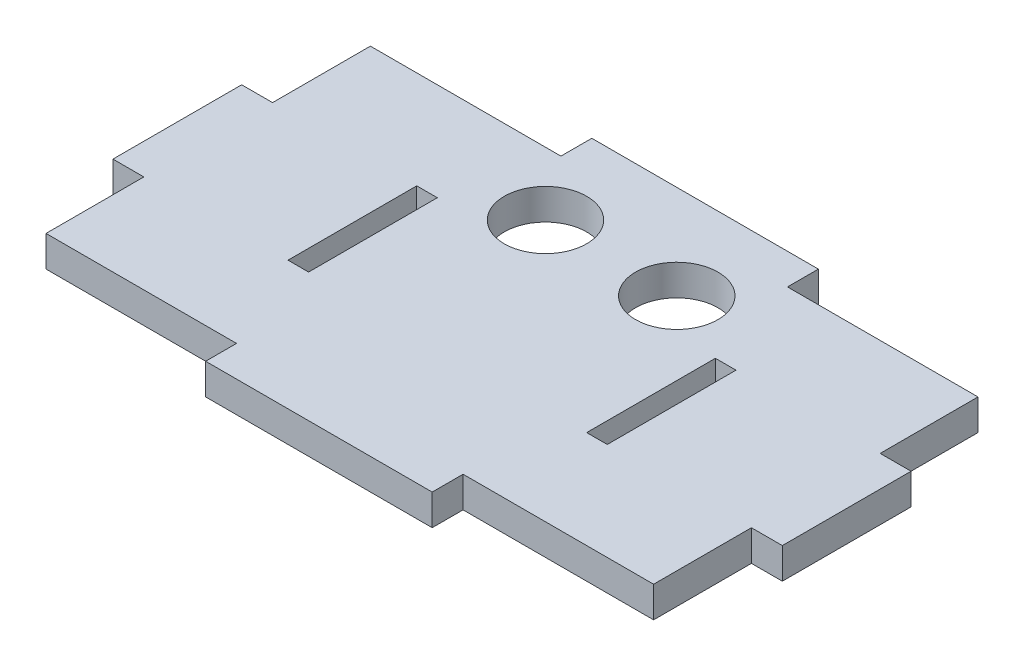
SolidWorks part; units mm, degrees
ref_plane "Front" through (0, 0, 0) normal (0, 0, 1) x (1, 0, 0)
ref_plane "Top" through (0, 0, 0) normal (0, 1, 0) x (1, 0, 0)
ref_plane "Right" through (0, 0, 0) normal (1, 0, 0) x (0, 0, -1)
sketch "Sketch1" plane through (0, 0, 0) normal (0, 1, 0) x (1, 0, 0)
  line L1 (0, 0) -> (130, 0)
  line L2 (0, 0) -> (0, 75)
  line L3 (0, 75) -> (130, 75)
  line L4 (130, 0) -> (130, 75)
  dimension "D1" = 130
  dimension "D2" = 75
extrude "Boss-Extrude1" add sketch "Sketch1" along normal blind 6
sketch "Sketch2" plane through (0, 6, 0) normal (0, 1, 0) x (1, 0, 0)
  line L0 (130, 75) -> (0, 75) construction
  line L1 (130, 0) -> (130, 75) construction
  circle A0 centre (52.25, 56.75) radius 8
  circle A1 centre (77.75, 56.75) radius 8
  dimension "D1" = 16
  dimension "D2" = 25.5
  dimension "D3" = 18.25
  dimension "D4" = 52.25
extrude "Cut-Extrude1" cut sketch "Sketch2" against normal blind 6
sketch "Sketch3" plane through (0, 6, 0) normal (0, 1, 0) x (1, 0, 0)
  line L0 (130, 75) -> (0, 75) construction
  line L1 (0, 0) -> (43, 0)
  line L2 (0, 0) -> (0, 6)
  line L3 (0, 6) -> (43, 6)
  line L4 (43, 0) -> (43, 6)
  line L5 (43, 0) -> (87, 0)
  line L6 (43, 0) -> (43, 6)
  line L7 (43, 6) -> (87, 6)
  line L8 (87, 0) -> (87, 6)
  line L9 (0, 0) -> (6, 0)
  line L10 (0, 0) -> (0, 25)
  line L11 (0, 25) -> (6, 25)
  line L12 (6, 0) -> (6, 25)
  line L13 (0, 25) -> (6, 25)
  line L14 (0, 25) -> (0, 50)
  line L15 (0, 50) -> (6, 50)
  line L16 (6, 25) -> (6, 50)
  line L17 (0, 50) -> (6, 50)
  line L18 (0, 50) -> (0, 75)
  line L19 (0, 75) -> (6, 75)
  line L20 (6, 50) -> (6, 75)
  line L21 (0, 0) -> (130, 0) construction
  line L22 (130, 75) -> (124, 75)
  line L23 (130, 75) -> (130, 50)
  line L24 (130, 50) -> (124, 50)
  line L25 (124, 75) -> (124, 50)
  line L26 (124, 50) -> (130, 50)
  line L27 (124, 50) -> (124, 25)
  line L28 (124, 25) -> (130, 25)
  line L29 (130, 50) -> (130, 25)
  line L30 (130, 25) -> (124, 25)
  line L31 (130, 25) -> (130, 0)
  line L32 (130, 0) -> (124, 0)
  line L33 (124, 25) -> (124, 0)
  line L35 (34, 75) -> (38, 75)
  line L36 (34, 75) -> (34, 50)
  line L37 (34, 50) -> (38, 50)
  line L38 (38, 75) -> (38, 50)
  line L39 (34, 50) -> (38, 50)
  line L40 (34, 50) -> (34, 25)
  line L41 (34, 25) -> (38, 25)
  line L42 (38, 50) -> (38, 25)
  line L43 (34, 25) -> (38, 25)
  line L44 (34, 25) -> (34, 0)
  line L45 (34, 0) -> (38, 0)
  line L46 (38, 25) -> (38, 0)
  line L47 (96, 75) -> (92, 75)
  line L48 (96, 75) -> (96, 50)
  line L49 (96, 50) -> (92, 50)
  line L50 (92, 75) -> (92, 50)
  line L51 (96, 50) -> (92, 50)
  line L52 (96, 50) -> (96, 25)
  line L53 (96, 25) -> (92, 25)
  line L54 (92, 50) -> (92, 25)
  line L55 (92, 25) -> (96, 25)
  line L56 (92, 25) -> (92, 0)
  line L57 (92, 0) -> (96, 0)
  line L58 (96, 25) -> (96, 0)
  line L59 (130, 0) -> (87, 0)
  line L60 (130, 0) -> (130, 6)
  line L61 (130, 6) -> (87, 6)
  line L62 (87, 0) -> (87, 6)
  line L63 (0, 75) -> (43, 75)
  line L64 (0, 75) -> (0, 69)
  line L65 (0, 69) -> (43, 69)
  line L66 (43, 75) -> (43, 69)
  line L67 (43, 75) -> (87, 75)
  line L68 (43, 75) -> (43, 69)
  line L69 (43, 69) -> (87, 69)
  line L70 (87, 75) -> (87, 69)
  line L71 (87, 69) -> (130, 69)
  line L72 (87, 69) -> (87, 75)
  line L73 (87, 75) -> (130, 75)
  line L74 (130, 69) -> (130, 75)
  line M45 (0, 75) -> (0, 0)
  line M46 (0, 0) -> (130, 0)
  line M47 (130, 0) -> (130, 75)
  line M48 (130, 75) -> (0, 75)
  dimension "D1" = 6
  dimension "D2" = 43
  dimension "D3" = 44
  dimension "D4" = 6
  dimension "D5" = 4
  dimension "D6" = 34
  dimension "D7" = 34
extrude "Cut-Extrude2" cut sketch "Sketch3" against normal through all contours L15 L20 M48 M45 | L3 L12 L11 M45 | L12 L3 M46 M45 | L44 L3 L12 L1 | L3 L46 L1 L4 | L46 L3 L44 M46 | L42 L37 L40 L41 | L49 L54 L53 L52 | L28 L33 M46 M47 | L25 L24 M48 M47 | L60 L59 L62 L61 | L64 L63 L66 L65 | L72 L71 L74 L73
